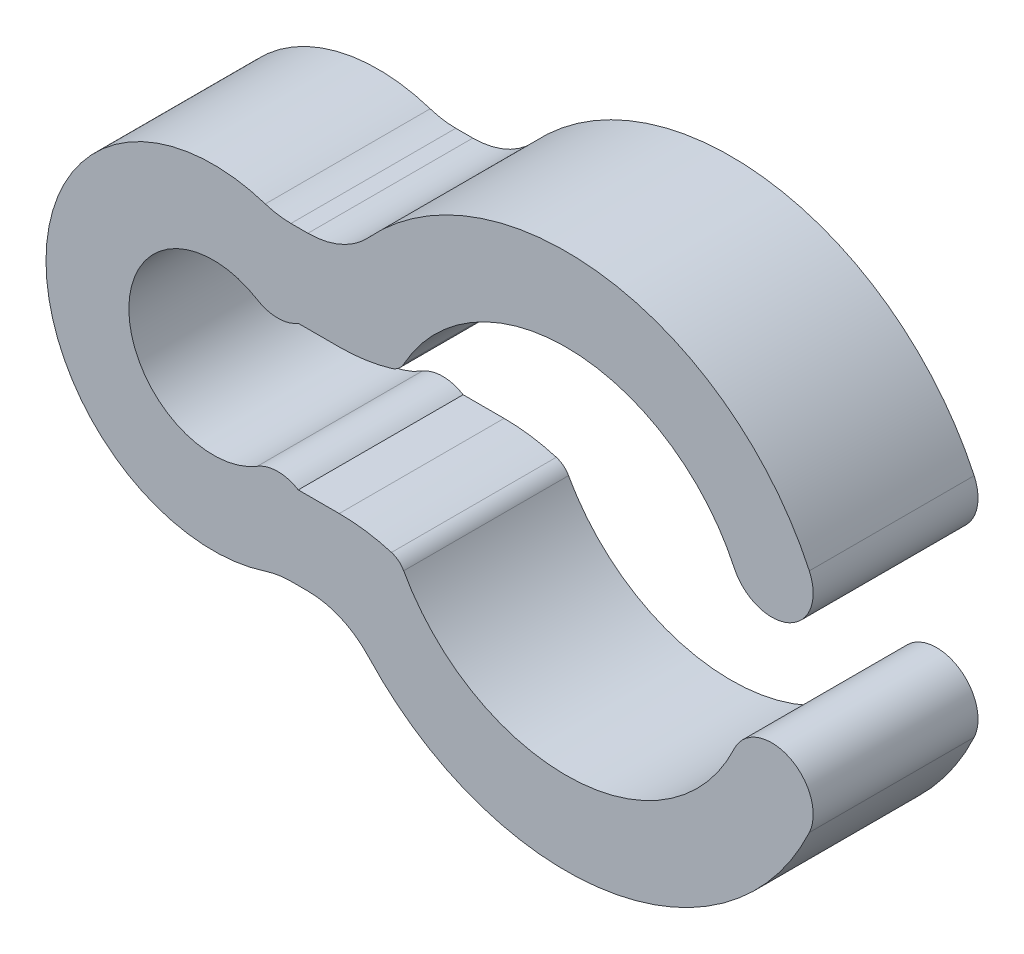
SolidWorks part; units mm, degrees
ref_plane "Front Plane" through (0, 0, 0) normal (0, 0, 1) x (1, 0, 0)
ref_plane "Top Plane" through (0, 0, 0) normal (0, 1, 0) x (1, 0, 0)
ref_plane "Right Plane" through (0, 0, 0) normal (1, 0, 0) x (0, 0, -1)
sketch "Sketch1" plane through (0, 0, 0) normal (0, 0, 1) x (1, 0, 0)
  line L10 (-6.6769, 3.76) -> (-6.2644, 3.76)
  line L21 (-6.4986, 1.75) -> (-5.505, 1.75)
  line L23 (-6.4986, -1.75) -> (-5.505, -1.75)
  line L24 (-6.6769, -3.76) -> (-6.2644, -3.76)
  arc A0 (4.0792, 1.9) -> (-3.9413, 2.1717) centre (0, 0) ccw
  arc A11 (-7.4923, 1.75) -> (-7.4923, -1.75) centre (-8.56, 0) ccw
  arc A12 (-7.2984, 3.859) -> (-7.2984, -3.859) centre (-8.56, 0) ccw
  arc A13 (-4.7921, -4.4063) -> (5.9013, -2.7487) centre (0, 0) ccw
  arc A16 (-3.9413, -2.1717) -> (4.0792, -1.9) centre (0, 0) ccw
  arc A19 (5.9013, 2.7487) -> (-4.7921, 4.4063) centre (0, 0) ccw
  arc A20 (4.0792, 1.9) -> (5.9013, 2.7487) centre (4.9902, 2.3243) ccw
  arc A21 (5.9013, -2.7487) -> (4.0792, -1.9) centre (4.9902, -2.3243) ccw
  arc A22 (-6.2644, 3.76) -> (-4.7921, 4.4063) centre (-6.2644, 5.76) ccw
  arc A23 (-6.6769, 3.76) -> (-7.2984, 3.859) centre (-6.6769, 5.76) cw
  arc A24 (-5.505, 1.75) -> (-4.2374, 1.9335) centre (-5.505, 6.2196) ccw
  arc A25 (-5.505, -1.75) -> (-4.2374, -1.9335) centre (-5.505, -6.2196) cw
  arc A26 (-6.6769, -3.76) -> (-7.2984, -3.859) centre (-6.6769, -5.76) ccw
  arc A27 (-6.2644, -3.76) -> (-4.7921, -4.4063) centre (-6.2644, -5.76) cw
  arc A28 (-7.4923, 1.75) -> (-6.4986, 1.75) centre (-6.9955, 2.5643) ccw
  arc A29 (-7.4923, -1.75) -> (-6.4986, -1.75) centre (-6.9955, -2.5643) cw
  arc A30 (-3.9413, -2.1717) -> (-4.2374, -1.9335) centre (-4.3792, -2.413) ccw
  arc A31 (-3.9413, 2.1717) -> (-4.2374, 1.9335) centre (-4.3792, 2.413) cw
extrude "Boss-Extrude1" add sketch "Sketch1" along normal blind 4
